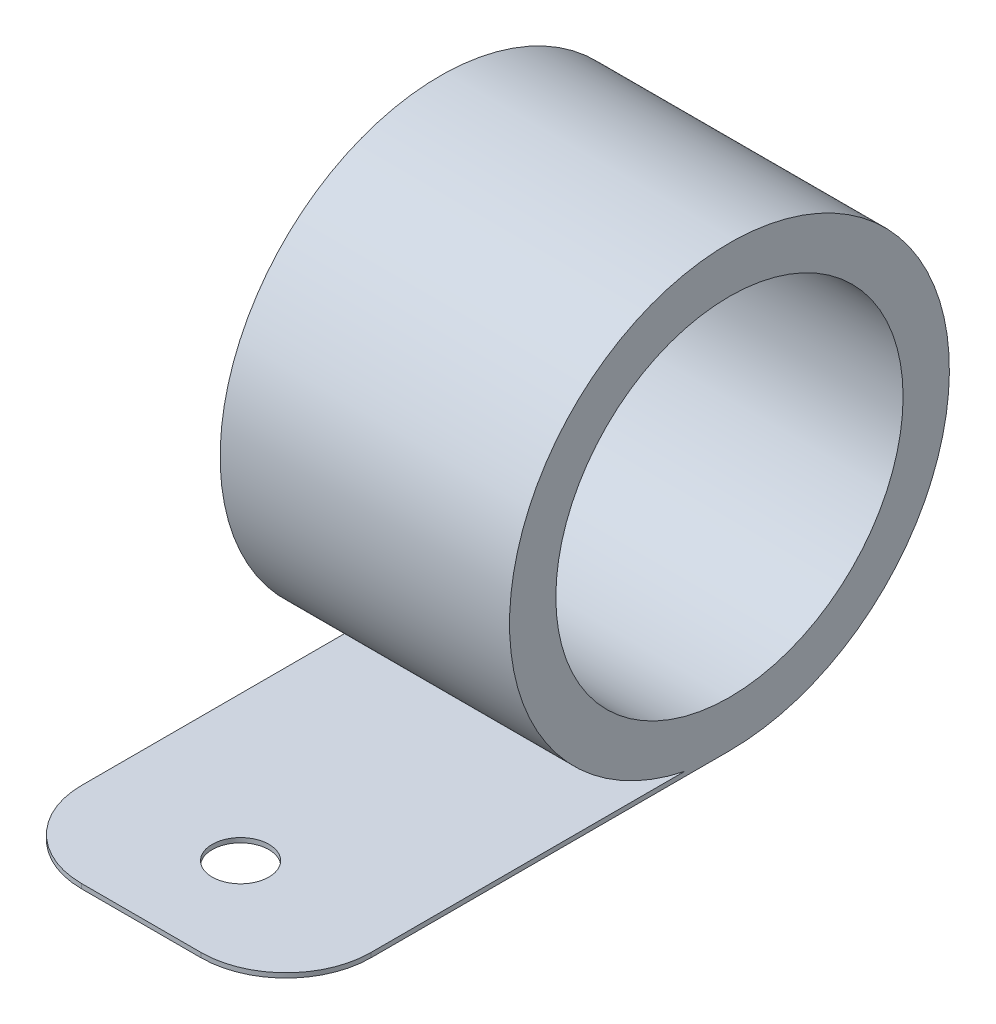
SolidWorks part; units mm, degrees
ref_plane "Front" through (0, 0, 0) normal (0, 0, 1) x (1, 0, 0)
ref_plane "Top" through (0, 0, 0) normal (0, 1, 0) x (1, 0, 0)
ref_plane "Right" through (0, 0, 0) normal (1, 0, 0) x (0, 0, -1)
sketch "Sketch1" plane through (0, 0, 0) normal (1, 0, 0) x (0, 0, -1)
  circle A0 centre (0, 0) radius 19.304
  circle A1 centre (0, 0) radius 15.24
  dimension "D1" = 38.608
  dimension "D2" = 30.48
extrude "Boss-Extrude1" add sketch "Sketch1" along normal mid plane 25.4
ref_plane "Plane1" through (0, -19.304, 0) normal (0, 1, 0) x (1, 0, 0)
sketch "Sketch2" plane through (0, -19.304, 0) normal (0, 1, 0) x (1, 0, 0)
  line L0 (12.7, -19.304) -> (12.7, 19.304) construction
  line L1 (12.7, 0) -> (-12.7, 0)
  line L2 (12.7, 0) -> (12.7, -38.9236)
  line L3 (12.7, -38.9236) -> (-12.7, -38.9236)
  line L4 (-12.7, 0) -> (-12.7, -38.9236)
extrude "Boss-Extrude2" add sketch "Sketch2" along normal blind 0.4064
sketch "Sketch3" plane through (0, -18.8976, 0) normal (0, 1, 0) x (1, 0, 0)
  line L0 (-12.7, -38.9236) -> (12.7, -38.9236) construction
  circle A0 centre (0, -30.2114) radius 2.4892
  dimension "D1" = 4.9784
  dimension "D2" = 8.7122
extrude "Cut-Extrude1" cut sketch "Sketch3" against normal through all both and the other way through all
fillet "Fillet1" radius 7.46 2 edges at (-12.7, -19.1008, 38.9236) (12.7, -19.1008, 38.9236)
